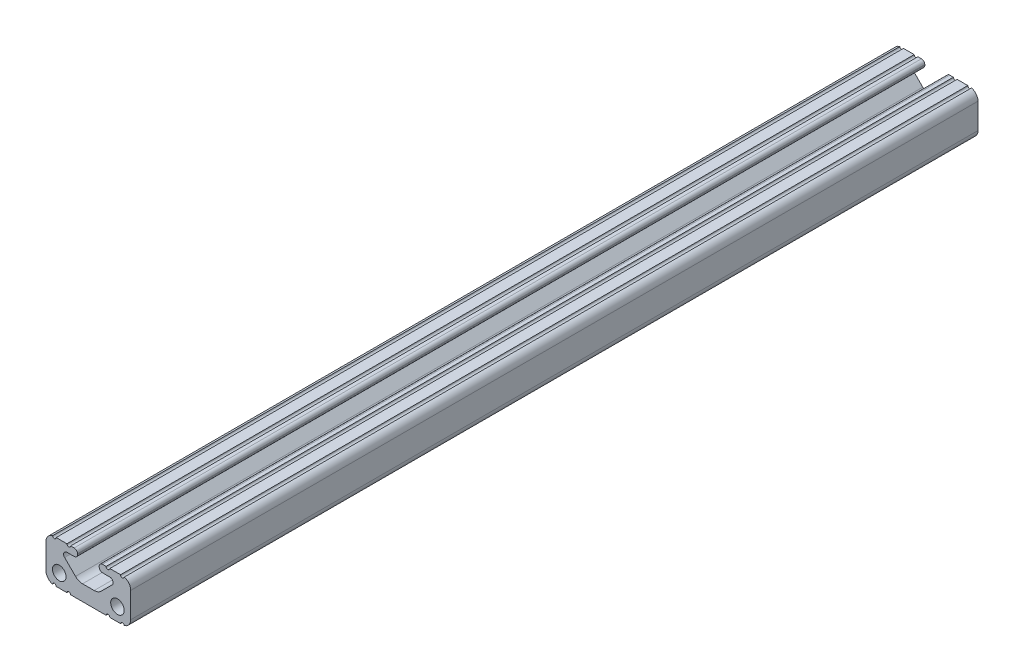
SolidWorks part; units mm, degrees
ref_plane "Front Plane" through (0, 0, 0) normal (0, 0, 1) x (1, 0, 0)
ref_plane "Top Plane" through (0, 0, 0) normal (0, 1, 0) x (1, 0, 0)
ref_plane "Right Plane" through (0, 0, 0) normal (1, 0, 0) x (0, 0, -1)
sketch "Sketch1" plane through (0, 0, 0) normal (0, 0, 1) x (1, 0, 0)
  line L0 (0, 6.35) -> (0, -6.35) construction
  line L1 (0, -6.35) -> (12.7, -6.35)
  line L2 (12.7, -6.35) -> (12.7, 6.35)
  line L3 (12.7, 6.35) -> (3.2512, 6.35)
  line L4 (3.2512, 6.35) -> (3.2512, 4.1402)
  line L5 (3.2512, 4.1402) -> (6.4224, 4.1402)
  line L6 (7.1255, 2.4426) -> (2.9811, -1.7018)
  line L7 (2.9811, -1.7018) -> (0, -1.7018)
  circle A0 centre (8.7249, -2.3876) radius 2.032
  arc A1 (6.4224, 4.1402) -> (7.1255, 2.4426) centre (6.4224, 3.1458) cw
  dimension "Center Hole Diameter" = 4.064
  dimension "D3" = 0.9944
  dimension "Rail Height" = 25.4
  dimension "Rail Width" = 12.7
  dimension "Hole CtoC" = 17.4498
  dimension "D1" = 3.9624
  dimension "T-Slot Width" = 6.5024
  dimension "Thickness" = 2.2098
  dimension "Inner Slot Width" = 14.8336
  dimension "Slot Depth" = 5.842
  dimension "D2" = 45
sketch "Sketch2" plane through (0, 0, 0) normal (1, 0, 0) x (0, 0, -1)
  line L0 (-152.4, -6.35) -> (152.4, -6.35) construction
  line L1 (-127, 0) -> (127, 0) construction
  dimension "Length" = 304.8
  dimension "D1" = 25.4
sketch "Sketch3" plane through (0, 0, 0) normal (0, 0, 1) x (1, 0, 0)
  line L0 (3.2512, 6.35) -> (3.2512, 4.1402) construction
  line L1 (12.7, 6.35) -> (3.2512, 6.35) construction
  line L2 (3.2512, 4.1402) -> (6.4224, 4.1402) construction
  line L3 (3.2512, 5.3556) -> (3.2512, 5.1346)
  line L4 (12.7, -6.35) -> (12.7, 6.35) construction
  line L5 (0, -6.35) -> (12.7, -6.35) construction
  line L6 (2.9811, -1.7018) -> (0, -1.7018) construction
  line L7 (7.1255, 2.4426) -> (2.9811, -1.7018) construction
  line L8 (0, -1.7018) -> (1.7454, -1.7018)
  line L9 (4.2456, 4.1402) -> (6.4224, 4.1402)
  line L10 (3.8549, -0.828) -> (7.1255, 2.4426)
  line L11 (0, -1.7018) -> (0, -6.35)
  line L12 (0, -6.35) -> (10.16, -6.35)
  line L13 (12.7, -3.81) -> (12.7, 3.81)
  line L14 (4.2456, 6.35) -> (10.16, 6.35)
  arc A0 (3.2512, 5.3556) -> (4.2456, 6.35) centre (4.2456, 5.3556) cw
  arc A1 (3.2512, 5.1346) -> (4.2456, 4.1402) centre (4.2456, 5.1346) ccw
  arc A2 (7.1255, 2.4426) -> (6.4224, 4.1402) centre (6.4224, 3.1458) ccw construction
  arc A3 (10.16, 6.35) -> (12.7, 3.81) centre (10.16, 3.81) cw
  arc A4 (10.16, -6.35) -> (12.7, -3.81) centre (10.16, -3.81) ccw
  arc A5 (7.1255, 2.4426) -> (6.4224, 4.1402) centre (6.4224, 3.1458) ccw
  circle A6 centre (8.7249, -2.3876) radius 2.032 construction
  circle A7 centre (8.7249, -2.3876) radius 2.032
  arc A8 (1.7454, -1.7018) -> (3.8549, -0.828) centre (1.7454, 1.2814) ccw
  dimension "D2" = 2.9832
extrude "Boss-Extrude1" add sketch "Sketch3" along normal mid plane 304.8
sketch "Sketch4" plane through (0, 0, 0) normal (0, 0, 1) x (1, 0, 0)
  line L0 (12.7, 6.35) -> (3.2512, 6.35) construction
  line L1 (0, -6.35) -> (12.7, -6.35) construction
  line L2 (10.7569, -2.3876) -> (10.7569, 6.35) construction
  line L3 (6.4224, 3.1458) -> (6.4224, 6.35) construction
  circle A0 centre (5.8699, 6.35) radius 0.5524
  circle A1 centre (10.2045, 6.35) radius 0.5524
  circle A2 centre (5.8699, -6.35) radius 0.5524
  circle A3 centre (10.2045, -6.35) radius 0.5524
  circle A4 centre (8.7249, -2.3876) radius 2.032 construction
  dimension "D1" = 1.1049
extrude "Cut-Extrude1" cut sketch "Sketch4" against normal through all both and the other way through all
mirror "Mirror1" about plane through (0, 0, 0) normal (1, 0, 0) of bodies 135
sketch "Sketch5" plane through (0, 0, 152.4) normal (0, 0, 1) x (1, 0, 0)
  line L16 (9.652, 6.35) -> (6.4224, 6.35)
  line L17 (5.3175, 6.35) -> (4.2456, 6.35)
  line L18 (3.2512, 5.3556) -> (3.2512, 5.1346)
  line L19 (4.2456, 4.1402) -> (6.4224, 4.1402)
  line L20 (7.1255, 2.4426) -> (3.8549, -0.828)
  line L21 (1.7454, -1.7018) -> (-1.7454, -1.7018)
  line L22 (-3.8549, -0.828) -> (-7.1255, 2.4426)
  line L23 (-6.4224, 4.1402) -> (-4.2456, 4.1402)
  line L24 (-3.2512, 5.1346) -> (-3.2512, 5.3556)
  line L25 (-4.2456, 6.35) -> (-5.3175, 6.35)
  line L26 (-6.4224, 6.35) -> (-9.652, 6.35)
  line L27 (-12.7, 3.81) -> (-12.7, -3.81)
  line L28 (-9.652, -6.35) -> (-6.4224, -6.35)
  line L29 (-5.3175, -6.35) -> (5.3175, -6.35)
  line L30 (6.4224, -6.35) -> (9.652, -6.35)
  line L31 (12.7, -3.81) -> (12.7, 3.81)
  line L32 (9.652, 6.35) -> (6.4224, 6.35)
  line L33 (5.3175, 6.35) -> (4.2456, 6.35)
  line L34 (3.2512, 5.3556) -> (3.2512, 5.1346)
  line L35 (4.2456, 4.1402) -> (6.4224, 4.1402)
  line L36 (7.1255, 2.4426) -> (3.8549, -0.828)
  line L37 (1.7454, -1.7018) -> (-1.7454, -1.7018)
  line L38 (-3.8549, -0.828) -> (-7.1255, 2.4426)
  line L39 (-6.4224, 4.1402) -> (-4.2456, 4.1402)
  line L40 (-3.2512, 5.1346) -> (-3.2512, 5.3556)
  line L41 (-4.2456, 6.35) -> (-5.3175, 6.35)
  line L42 (-6.4224, 6.35) -> (-9.652, 6.35)
  line L43 (-12.7, 3.81) -> (-12.7, -3.81)
  line L44 (-9.652, -6.35) -> (-6.4224, -6.35)
  line L45 (-5.3175, -6.35) -> (5.3175, -6.35)
  line L46 (6.4224, -6.35) -> (9.652, -6.35)
  line L47 (12.7, -3.81) -> (12.7, 3.81)
  arc A20 (12.7, 3.81) -> (10.7524, 6.2799) centre (10.16, 3.81) ccw
  arc A21 (9.652, 6.35) -> (10.7524, 6.2799) centre (10.2045, 6.35) ccw
  arc A22 (5.3175, 6.35) -> (6.4224, 6.35) centre (5.8699, 6.35) ccw
  arc A23 (4.2456, 6.35) -> (3.2512, 5.3556) centre (4.2456, 5.3556) ccw
  arc A24 (3.2512, 5.1346) -> (4.2456, 4.1402) centre (4.2456, 5.1346) ccw
  arc A25 (7.1255, 2.4426) -> (6.4224, 4.1402) centre (6.4224, 3.1458) ccw
  arc A26 (1.7454, -1.7018) -> (3.8549, -0.828) centre (1.7454, 1.2814) ccw
  arc A27 (-3.8549, -0.828) -> (-1.7454, -1.7018) centre (-1.7454, 1.2814) ccw
  arc A28 (-6.4224, 4.1402) -> (-7.1255, 2.4426) centre (-6.4224, 3.1458) ccw
  arc A29 (-4.2456, 4.1402) -> (-3.2512, 5.1346) centre (-4.2456, 5.1346) ccw
  arc A30 (-3.2512, 5.3556) -> (-4.2456, 6.35) centre (-4.2456, 5.3556) ccw
  arc A31 (-6.4224, 6.35) -> (-5.3175, 6.35) centre (-5.8699, 6.35) ccw
  arc A32 (-10.7524, 6.2799) -> (-9.652, 6.35) centre (-10.2045, 6.35) ccw
  arc A33 (-10.7524, 6.2799) -> (-12.7, 3.81) centre (-10.16, 3.81) ccw
  arc A34 (-12.7, -3.81) -> (-10.7524, -6.2799) centre (-10.16, -3.81) ccw
  arc A35 (-9.652, -6.35) -> (-10.7524, -6.2799) centre (-10.2045, -6.35) ccw
  arc A36 (-5.3175, -6.35) -> (-6.4224, -6.35) centre (-5.8699, -6.35) ccw
  arc A37 (6.4224, -6.35) -> (5.3175, -6.35) centre (5.8699, -6.35) ccw
  arc A38 (10.7524, -6.2799) -> (9.652, -6.35) centre (10.2045, -6.35) ccw
  arc A39 (10.7524, -6.2799) -> (12.7, -3.81) centre (10.16, -3.81) ccw
  arc A40 (12.7, 3.81) -> (10.7524, 6.2799) centre (10.16, 3.81) ccw
  arc A41 (9.652, 6.35) -> (10.7524, 6.2799) centre (10.2045, 6.35) ccw
  arc A42 (5.3175, 6.35) -> (6.4224, 6.35) centre (5.8699, 6.35) ccw
  arc A43 (4.2456, 6.35) -> (3.2512, 5.3556) centre (4.2456, 5.3556) ccw
  arc A44 (3.2512, 5.1346) -> (4.2456, 4.1402) centre (4.2456, 5.1346) ccw
  arc A45 (7.1255, 2.4426) -> (6.4224, 4.1402) centre (6.4224, 3.1458) ccw
  arc A46 (1.7454, -1.7018) -> (3.8549, -0.828) centre (1.7454, 1.2814) ccw
  arc A47 (-3.8549, -0.828) -> (-1.7454, -1.7018) centre (-1.7454, 1.2814) ccw
  arc A48 (-6.4224, 4.1402) -> (-7.1255, 2.4426) centre (-6.4224, 3.1458) ccw
  arc A49 (-4.2456, 4.1402) -> (-3.2512, 5.1346) centre (-4.2456, 5.1346) ccw
  arc A50 (-3.2512, 5.3556) -> (-4.2456, 6.35) centre (-4.2456, 5.3556) ccw
  arc A51 (-6.4224, 6.35) -> (-5.3175, 6.35) centre (-5.8699, 6.35) ccw
  arc A52 (-10.7524, 6.2799) -> (-9.652, 6.35) centre (-10.2045, 6.35) ccw
  arc A53 (-10.7524, 6.2799) -> (-12.7, 3.81) centre (-10.16, 3.81) ccw
  arc A54 (-12.7, -3.81) -> (-10.7524, -6.2799) centre (-10.16, -3.81) ccw
  arc A55 (-9.652, -6.35) -> (-10.7524, -6.2799) centre (-10.2045, -6.35) ccw
  arc A56 (-5.3175, -6.35) -> (-6.4224, -6.35) centre (-5.8699, -6.35) ccw
  arc A57 (6.4224, -6.35) -> (5.3175, -6.35) centre (5.8699, -6.35) ccw
  arc A58 (10.7524, -6.2799) -> (9.652, -6.35) centre (10.2045, -6.35) ccw
  arc A59 (10.7524, -6.2799) -> (12.7, -3.81) centre (10.16, -3.81) ccw
  dimension "D1" = 0
extrude "Cut-Extrude2" cut sketch "Sketch5" against normal offset from surface (50.8 mm away) 254 up to face at (0, 1.3921, -152.4)
equation "\"D3@Sketch1\"=\"Thickness@Sketch1\"*0.45"
equation "\"D1@Sketch3\"=\"Rail Width@Sketch1\"*0.2"
equation "\"D2@Sketch3\"=\"D3@Sketch1\"*3"
equation "\"D1@Boss-Extrude1\"=\"length@sketch2\""
equation "\"D1@Sketch4\"=\"Thickness@Sketch1\"*0.5"
